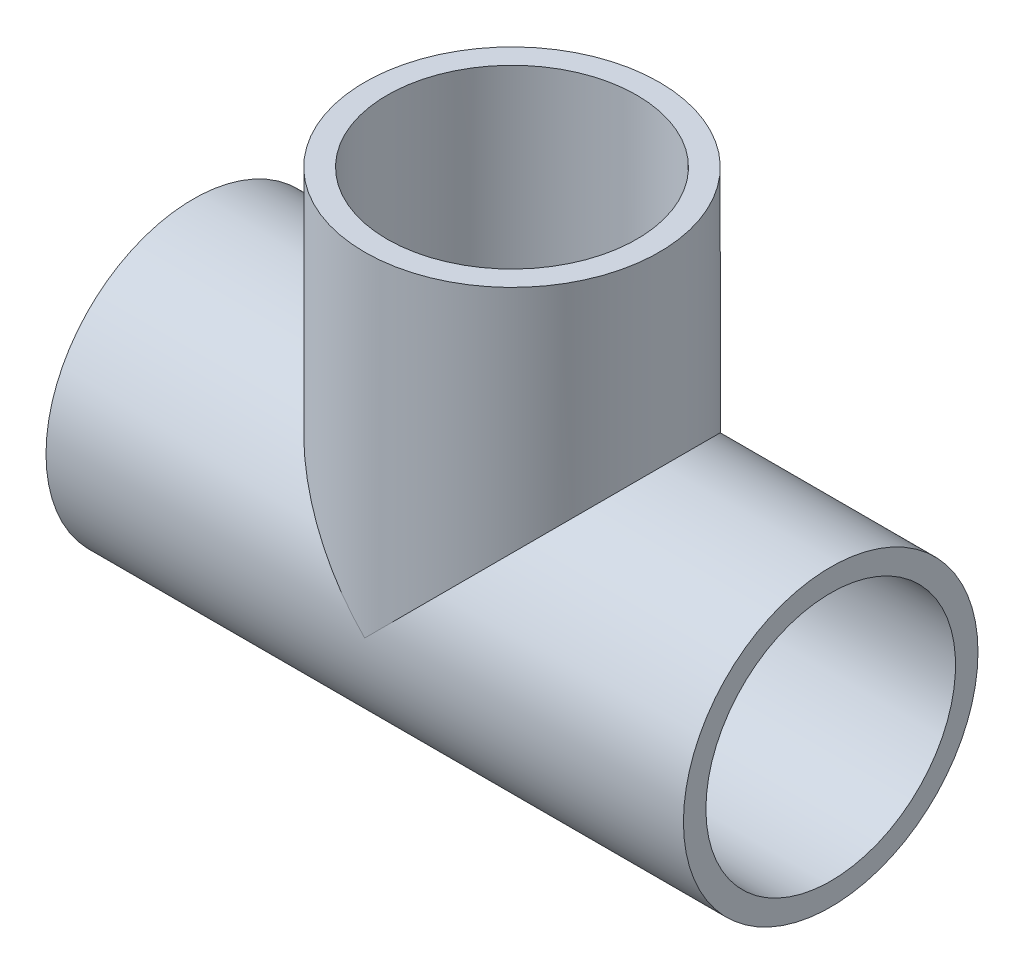
SolidWorks part; units mm, degrees
ref_plane "Front" through (0, 0, 0) normal (0, 0, 1) x (1, 0, 0)
ref_plane "Top" through (0, 0, 0) normal (0, 1, 0) x (1, 0, 0)
ref_plane "Right" through (0, 0, 0) normal (1, 0, 0) x (0, 0, -1)
sketch "Croquis1" plane through (0, 0, 0) normal (1, 0, 0) x (0, 0, -1)
  circle A0 centre (0, 0) radius 44.45
  circle A1 centre (0, 0) radius 52.45
  dimension "D1" = 88.9
  dimension "D2" = 8
extrude "Saliente-Extruir1" add sketch "Croquis1" along normal blind 227
sketch "Croquis2" plane through (0, 0, 0) normal (0, 1, 0) x (1, 0, 0)
  line L0 (0, 0) -> (227, 0) construction
  line L1 (227, -52.45) -> (227, 52.45) construction
  circle A0 centre (113.5, 0) radius 44.45
  circle A1 centre (113.5, 0) radius 52.45
  dimension "D1" = 8
  dimension "D2" = 88.9
extrude "Saliente-Extruir2" add sketch "Croquis2" along normal blind 119
sketch "Croquis3" plane through (0, 0, 0) normal (-1, 0, 0) x (0, 0, 1)
  circle A0 centre (0, 0) radius 44.45
  dimension "D1" = 88.9
extrude "Cortar-Extruir1" cut sketch "Croquis3" against normal up to surface (227 mm away) up to face at (227, 0, -52.45)
